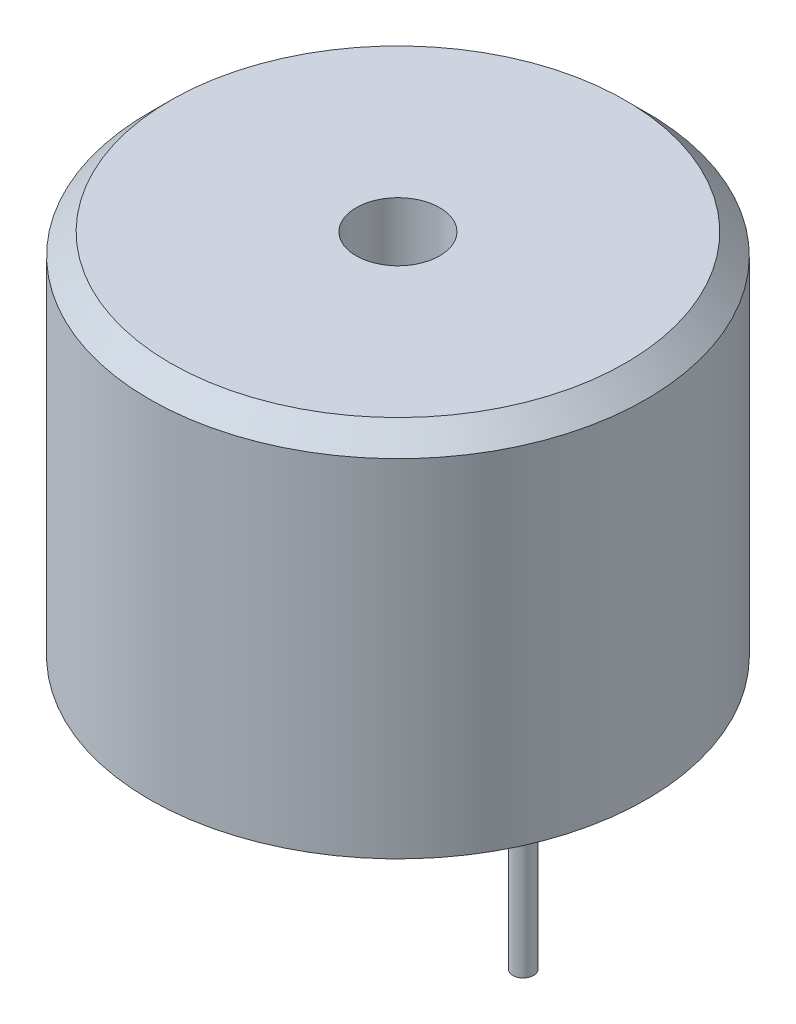
SolidWorks part; units mm, degrees
ref_plane "Front Plane" through (0, 0, 0) normal (0, 0, 1) x (1, 0, 0)
ref_plane "Top Plane" through (0, 0, 0) normal (0, 1, 0) x (1, 0, 0)
ref_plane "Right Plane" through (0, 0, 0) normal (1, 0, 0) x (0, 0, -1)
sketch "Sketch1" plane through (0, 0, 0) normal (0, 1, 0) x (1, 0, 0)
  circle A0 centre (0, 0) radius 5.95
  dimension "D1" = 11.9
extrude "Boss-Extrude1" add sketch "Sketch1" along normal blind 8.8
sketch "Sketch2" plane through (0, 8.8, 0) normal (0, 1, 0) x (1, 0, 0)
  circle A0 centre (0, 0) radius 1
  dimension "D1" = 2
extrude "Cut-Extrude1" cut sketch "Sketch2" against normal blind 2
chamfer "Chamfer1" distance 0.5 angle 45 1 edges at (0, 8.8, 5.95)
sketch "Sketch3" plane through (0, 0, 0) normal (0, -1, 0) x (1, 0, 0)
  line L0 (6.49, 0) -> (-6.49, 0) construction
  circle A0 centre (-3, 0) radius 0.25
  dimension "D2" = 0.5
  dimension "D1" = 3
extrude "Boss-Extrude2" add sketch "Sketch3" along normal blind 5
mirror "Mirror1" about plane through (0, 0, 0) normal (1, 0, 0) of "Boss-Extrude2"
